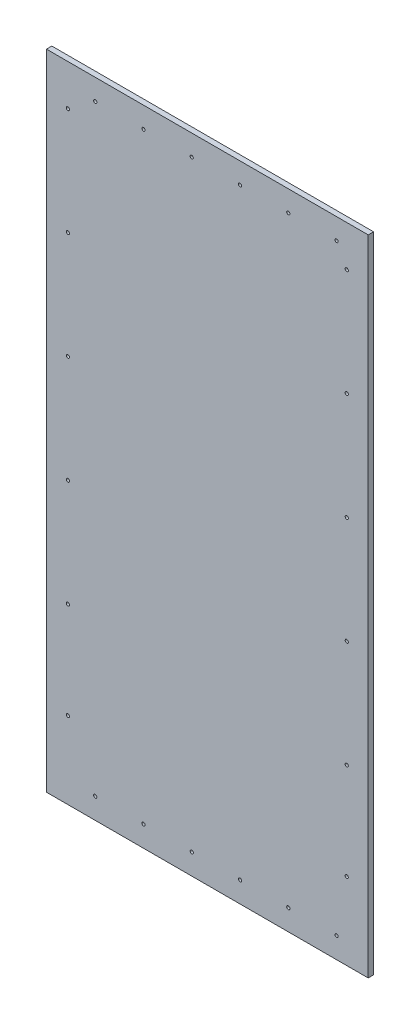
SolidWorks part; units mm, degrees
ref_plane "Alzado" through (0, 0, 0) normal (0, 0, 1) x (1, 0, 0)
ref_plane "Planta" through (0, 0, 0) normal (0, 1, 0) x (1, 0, 0)
ref_plane "Vista lateral" through (0, 0, 0) normal (1, 0, 0) x (0, 0, -1)
sketch "Croquis1" plane through (0, 0, 0) normal (0, 0, 1) x (1, 0, 0)
  line L1 (-150, 300) -> (150, 300)
  line L2 (-150, 300) -> (-150, -300)
  line L3 (-150, -300) -> (150, -300)
  line L4 (150, 300) -> (150, -300)
  line L5 (-150, 300) -> (150, -300) construction
  line L6 (-150, -300) -> (150, 300) construction
  point P0 (0, 0)
  dimension "D1" = 600
  dimension "D2" = 300
extrude "Saliente-Extruir1" add sketch "Croquis1" along normal blind 5
sketch "Croquis2" plane through (0, 0, 5) normal (0, 0, 1) x (1, 0, 0)
  line L0 (-104.5, 300) -> (-104.5, 280.5) construction
  line L1 (150, 300) -> (-150, 300) construction
  line L2 (-104.5, 280.5) -> (-150, 280.5) construction
  line L3 (-150, 300) -> (-150, -300) construction
  line L4 (-104.5, 280.5) -> (-59.5, 280.5) construction
  line L5 (-59.5, 280.5) -> (-14.5, 280.5) construction
  line L6 (-14.5, 280.5) -> (30.5, 280.5) construction
  line L7 (30.5, 280.5) -> (75.5, 280.5) construction
  line L8 (75.5, 280.5) -> (120.5, 280.5) construction
  line L9 (-150, 0) -> (150, 0) construction
  line L10 (150, -300) -> (150, 300) construction
  circle A0 centre (-104.5, 280.5) radius 1.5
  circle A1 centre (-59.5, 280.5) radius 1.5
  circle A2 centre (-14.5, 280.5) radius 1.5
  circle A3 centre (30.5, 280.5) radius 1.5
  circle A4 centre (75.5, 280.5) radius 1.5
  circle A5 centre (120.5, 280.5) radius 1.5
  circle A6 centre (120.5, -280.5) radius 1.5
  circle A7 centre (75.5, -280.5) radius 1.5
  circle A8 centre (30.5, -280.5) radius 1.5
  circle A9 centre (-14.5, -280.5) radius 1.5
  circle A10 centre (-59.5, -280.5) radius 1.5
  circle A11 centre (-104.5, -280.5) radius 1.5
  dimension "D2" = 3
  dimension "D5" = 3
  dimension "D7" = 3
  dimension "D9" = 3
  dimension "D11" = 3
  dimension "D13" = 3
  dimension "D1" = 19.5
  dimension "D3" = 45.5
  dimension "D4" = 45
  dimension "D6" = 45
  dimension "D8" = 45
  dimension "D10" = 45
  dimension "D12" = 45
extrude "Cortar-Extruir1" cut sketch "Croquis2" against normal blind 5
sketch "Croquis3" plane through (0, 0, 5) normal (0, 0, 1) x (1, 0, 0)
  line L0 (-130, 261.88) -> (-130, 300) construction
  line L1 (150, 300) -> (-150, 300) construction
  line L2 (-130, 261.88) -> (-150, 261.88) construction
  line L3 (-150, 300) -> (-150, -300) construction
  line L4 (-130, 261.88) -> (-130, 161.88) construction
  line L5 (-130, 161.88) -> (-130, 61.88) construction
  line L6 (-130, 61.88) -> (-130, -38.12) construction
  line L7 (-130, -38.12) -> (-130, -138.12) construction
  line L8 (-130, -138.12) -> (-130, -228.12) construction
  line L9 (0, 300) -> (0, -300) construction
  line L10 (-150, -300) -> (150, -300) construction
  circle A0 centre (-130, 261.88) radius 1.5
  circle A1 centre (-130, 161.88) radius 1.5
  circle A2 centre (-130, 61.88) radius 1.5
  circle A3 centre (-130, -38.12) radius 1.5
  circle A4 centre (-130, -138.12) radius 1.5
  circle A5 centre (-130, -228.12) radius 1.5
  circle A6 centre (130, -228.12) radius 1.5
  circle A7 centre (130, -138.12) radius 1.5
  circle A8 centre (130, -38.12) radius 1.5
  circle A9 centre (130, 61.88) radius 1.5
  circle A10 centre (130, 161.88) radius 1.5
  circle A11 centre (130, 261.88) radius 1.5
  point P34 (0, 0)
  dimension "D3" = 3
  dimension "D5" = 3
  dimension "D7" = 3
  dimension "D9" = 3
  dimension "D11" = 3
  dimension "D13" = 3
  dimension "D1" = 38.12
  dimension "D2" = 20
  dimension "D4" = 100
  dimension "D6" = 100
  dimension "D8" = 100
  dimension "D10" = 100
  dimension "D12" = 90
extrude "Cortar-Extruir2" cut sketch "Croquis3" against normal blind 5
